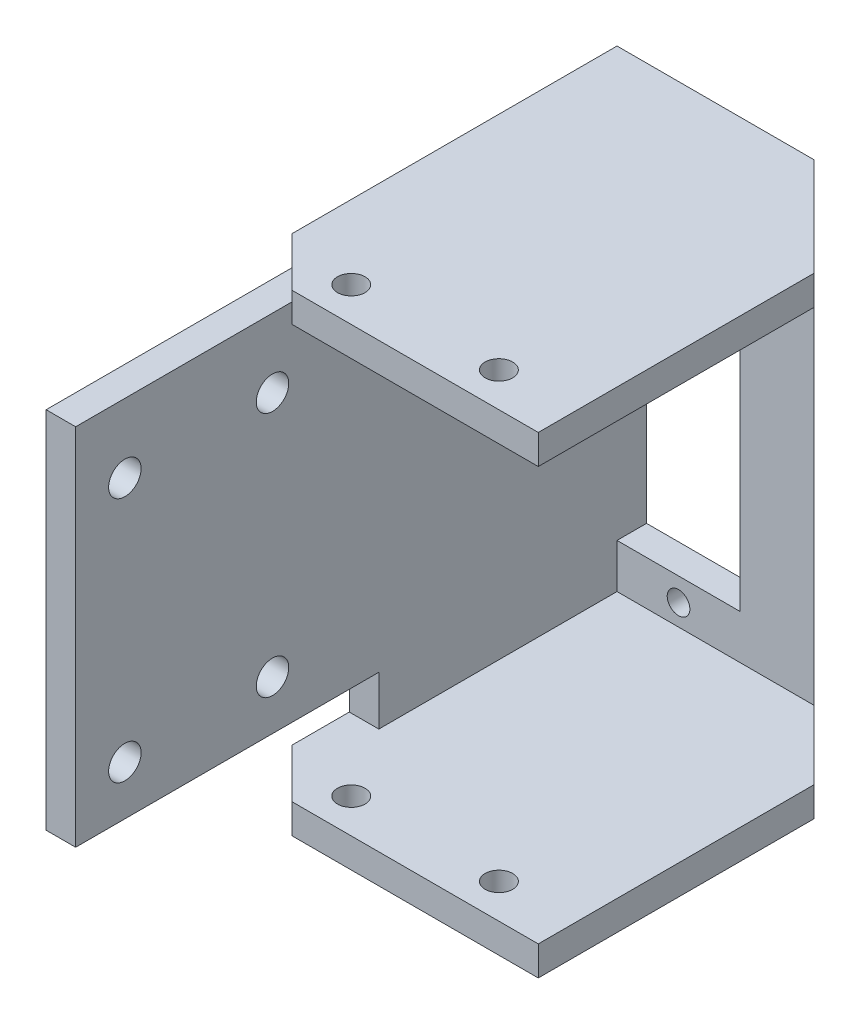
SolidWorks part; units mm, degrees
ref_plane "前视基准面" through (0, 0, 0) normal (0, 0, 1) x (1, 0, 0)
ref_plane "上视基准面" through (0, 0, 0) normal (0, 1, 0) x (1, 0, 0)
ref_plane "右视基准面" through (0, 0, 0) normal (1, 0, 0) x (0, 0, -1)
other "Configuration Table"
sketch "草图1" plane through (0, 0, 0) normal (0, 0, 1) x (1, 0, 0)
  line L1 (0, 0) -> (30, 0)
  line L2 (0, 0) -> (0, 48)
  line L3 (0, 48) -> (30, 48)
  line L4 (30, 0) -> (30, 48)
  dimension "D1" = 48
  dimension "D2" = 30
extrude "凸台-拉伸1" add sketch "草图1" along normal blind 3
sketch "草图3" plane through (0, 0, 3) normal (0, 0, 1) x (1, 0, 0)
  line L0 (30, 0) -> (30, 48) construction
  line L1 (0, 48) -> (30, 48)
  line L2 (0, 48) -> (0, 45)
  line L3 (0, 45) -> (30, 45)
  line L4 (30, 48) -> (30, 45)
  line L6 (0, 0) -> (30, 0)
  line L7 (0, 0) -> (0, 3)
  line L8 (0, 3) -> (30, 3)
  line L9 (30, 0) -> (30, 3)
  dimension "D1" = 3
  dimension "D2" = 3
extrude "凸台-拉伸2" add sketch "草图3" along normal blind 35
sketch "草图4" plane through (0, 0, 0) normal (0, 0, -1) x (-1, 0, 0)
  line L0 (0, 48) -> (0, 0) construction
  circle A1 centre (-9.25, 37.75) radius 2
  dimension "D1" = 4
  dimension "D2" = 9.25
sketch "草图5" plane through (0, 0, 0) normal (0, -1, 0) x (1, 0, 0)
  line L0 (0, 33) -> (5, 38)
  line L1 (0, 38) -> (0, 0) construction
  line L2 (0, 38) -> (30, 38) construction
  line L3 (5, 38) -> (0, 38)
  line L4 (0, 38) -> (0, 33)
  dimension "D1" = 45
  dimension "D2" = 5
extrude "切除-拉伸2" cut sketch "草图5" against normal through all
sketch "草图6" plane through (0, 0, 0) normal (0, -1, 0) x (1, 0, 0)
  line L0 (20, 0) -> (30, 10)
  line L1 (0, 0) -> (30, 0) construction
  line L2 (30, 38) -> (30, 0) construction
  line L3 (30, 10) -> (30, 0)
  line L4 (30, 0) -> (20, 0)
  dimension "D1" = 45
  dimension "D2" = 10
extrude "切除-拉伸3" cut sketch "草图6" against normal through all
sketch "草图7" plane through (0, 0, 3) normal (0, 0, 1) x (1, 0, 0)
  line L1 (0, 3) -> (3, 3)
  line L2 (0, 3) -> (0, 45)
  line L3 (0, 45) -> (3, 45)
  line L4 (3, 3) -> (3, 45)
  line L6 (5, 45) -> (0, 45) construction
extrude "凸台-拉伸3" add sketch "草图7" along normal blind 25
sketch "草图10" plane through (0, 0, 3) normal (0, 0, 1) x (1, 0, 0)
  line L0 (5, 45) -> (30, 45) construction
  line L1 (20.5, 12.8) -> (16.5, 12.8)
  line L2 (20.5, 12.8) -> (20.5, 45)
  line L3 (20.5, 45) -> (16.5, 45)
  line L4 (16.5, 12.8) -> (16.5, 45)
  dimension "D1" = 4
sketch "草图12" plane through (3, 0, 0) normal (1, 0, 0) x (0, 0, -1)
  line L1 (-23.1624, 31.4269) -> (-9.1105, 31.4269)
  line L2 (-23.1624, 31.4269) -> (-23.1624, 41.7502)
  line L3 (-23.1624, 41.7502) -> (-9.1105, 41.7502)
  line L4 (-9.1105, 31.4269) -> (-9.1105, 41.7502)
sketch "草图14" plane through (0, 0, 28) normal (0, 0, 1) x (1, 0, 0)
  line L4 (0, 45) -> (0, 3)
  line L5 (0, 3) -> (3, 3)
  line L6 (3, 3) -> (3, 45)
  line L7 (3, 45) -> (0, 45)
  line L8 (0, 45) -> (0, 3)
  line L10 (3, 3) -> (3, 45)
  line L11 (3, 45) -> (0, 45)
  line L12 (0, 3) -> (3, 3)
  dimension "D1" = 0
extrude "凸台-拉伸6" add sketch "草图14" along normal blind 30
sketch "草图15" plane through (0, 0, 0) normal (-1, 0, 0) x (0, 0, 1)
  circle A0 centre (38, 13) radius 1.65
  circle A1 centre (38, 38) radius 1.65
  circle A2 centre (53, 38) radius 1.65
  circle A3 centre (53, 13) radius 1.65
extrude "切除-拉伸6" cut sketch "草图15" against normal blind 4
sketch "草图16" plane through (0, 0, 3) normal (0, 0, 1) x (1, 0, 0)
  line L0 (3, 3) -> (3, 45) construction
  line L1 (15.5, 7.5) -> (3, 7.5)
  line L2 (15.5, 7.5) -> (15.5, 30.5)
  line L3 (15.5, 30.5) -> (3, 30.5)
  line L4 (3, 7.5) -> (3, 30.5)
  line L5 (3, 30.5) -> (15.5, 30.5) construction
  circle A0 centre (9.25, 32.85) radius 1.15
  circle A1 centre (9.25, 5.15) radius 1.15
  dimension "D1" = 2.3
  dimension "D2" = 2.3
extrude "切除-拉伸7" cut sketch "草图16" against normal blind 10
sketch "草图17" plane through (0, 0, 0) normal (-1, 0, 0) x (0, 0, 1)
  line L1 (58, 3) -> (27.2, 3)
  line L2 (58, 3) -> (58, 8)
  line L3 (58, 8) -> (27.2, 8)
  line L4 (27.2, 3) -> (27.2, 8)
extrude "切除-拉伸8" cut sketch "草图17" against normal blind 10
sketch "草图18" plane through (0, 48, 0) normal (0, 1, 0) x (1, 0, 0)
  line L0 (0, 0) -> (0, 9)
  line L1 (0, 9) -> (20, 9)
  line L2 (20, 9) -> (20, 0)
  line L3 (20, 0) -> (17, 0)
  line L4 (20, 0) -> (0, 0) construction
  line L5 (17, 0) -> (17, 6)
  line L6 (17, 6) -> (3, 6)
  line L7 (3, 6) -> (3, 0)
  line L8 (3, 0) -> (0, 0)
  point P11 (3, 7.9826)
  dimension "D1" = 3
  dimension "D2" = 3
  dimension "D3" = 9
  dimension "D4" = 3
sketch "草图19" plane through (0, 0, 0) normal (0, 0, -1) x (-1, 0, 0)
  point P3 (38.6544, 37.75)
sketch "草图20" plane through (0, 0, 0) normal (0, -1, 0) x (1, 0, 0)
  circle A1 centre (22.5, 34.5) radius 1.4
  circle A3 centre (7.5, 34.5) radius 1.4
  point P4 (0, 0)
  dimension "D1" = 2.8
  dimension "D2" = 2.8
extrude "切除-拉伸11" cut sketch "草图20" against normal through all
sketch "草图22" plane through (0, 0, 0) normal (0, 0, -1) x (-1, 0, 0)
  line L0 (-9.25, 5.15) -> (-9.25, 53.4853) construction
  circle A0 centre (-9.25, 37.75) radius 2
  circle A1 centre (-9.25, 13.75) radius 2 construction
  dimension "D1" = 24
  dimension "D2" = 4
extrude "切除-拉伸12" cut sketch "草图22" against normal up to next
sketch "草图23" plane through (0, 0, 3) normal (0, 0, 1) x (1, 0, 0)
  line L1 (6.3738, 35.5569) -> (11.9282, 35.5569)
  line L2 (6.3738, 35.5569) -> (6.3738, 40.2313)
  line L3 (6.3738, 40.2313) -> (11.9282, 40.2313)
  line L4 (11.9282, 35.5569) -> (11.9282, 40.2313)
  circle A0 centre (9.25, 37.75) radius 2 construction
  circle A1 centre (9.25, 37.75) radius 2
extrude "凸台-拉伸9" add sketch "草图23" along normal blind 3
